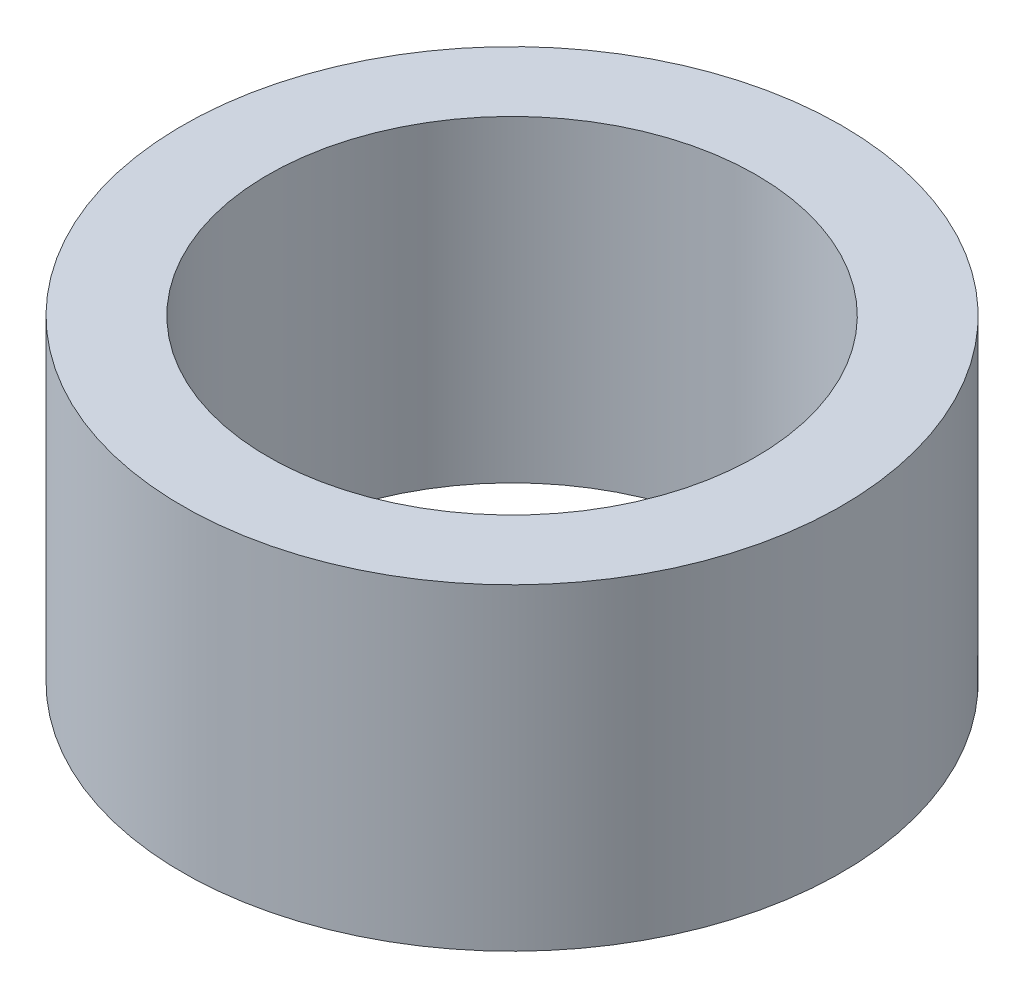
SolidWorks part; units mm, degrees
ref_plane "Front Plane" through (0, 0, 0) normal (0, 0, 1) x (1, 0, 0)
ref_plane "Top Plane" through (0, 0, 0) normal (0, 1, 0) x (1, 0, 0)
ref_plane "Right Plane" through (0, 0, 0) normal (1, 0, 0) x (0, 0, -1)
sketch "Sketch1" plane through (0, 0, 0) normal (0, 1, 0) x (1, 0, 0)
  circle A0 centre (0, 0) radius 5
  circle A1 centre (0, 0) radius 6.75
  dimension "D1" = 13.5
  dimension "D2" = 10
extrude "Boss-Extrude1" add sketch "Sketch1" along normal blind 6.5
